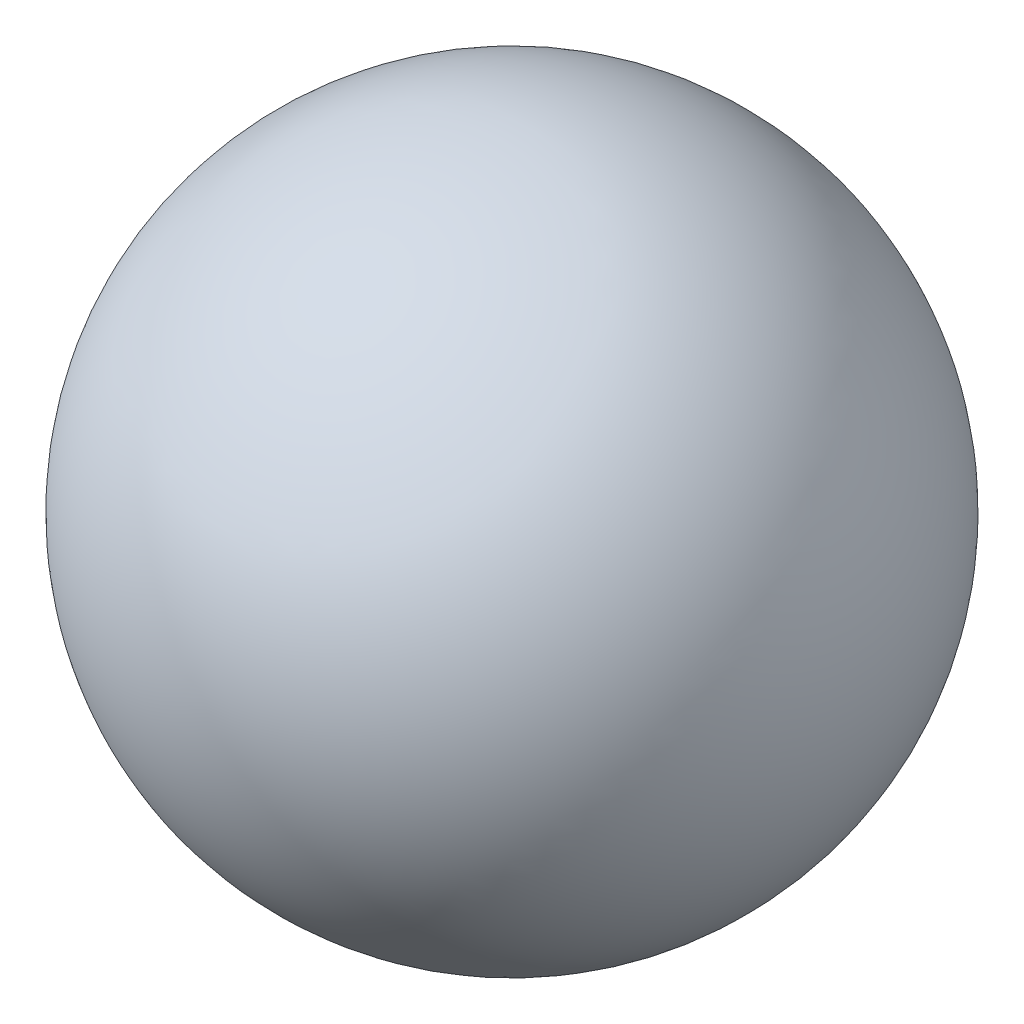
SolidWorks part; units mm, degrees
ref_plane "Front Plane" through (0, 0, 0) normal (0, 0, 1) x (1, 0, 0)
ref_plane "Top Plane" through (0, 0, 0) normal (0, 1, 0) x (1, 0, 0)
ref_plane "Right Plane" through (0, 0, 0) normal (1, 0, 0) x (0, 0, -1)
sketch "Sketch1" plane through (0, 0, 0) normal (0, 1, 0) x (1, 0, 0)
  line L0 (0, 29.571) -> (0, -29.571) construction
  arc A0 (0, 29.571) -> (0, -29.571) centre (0, 0) ccw
  dimension "D1" = 59.1419
revolve "Revolve-Thin1" add sketch "Sketch1" angle 360 about L0
